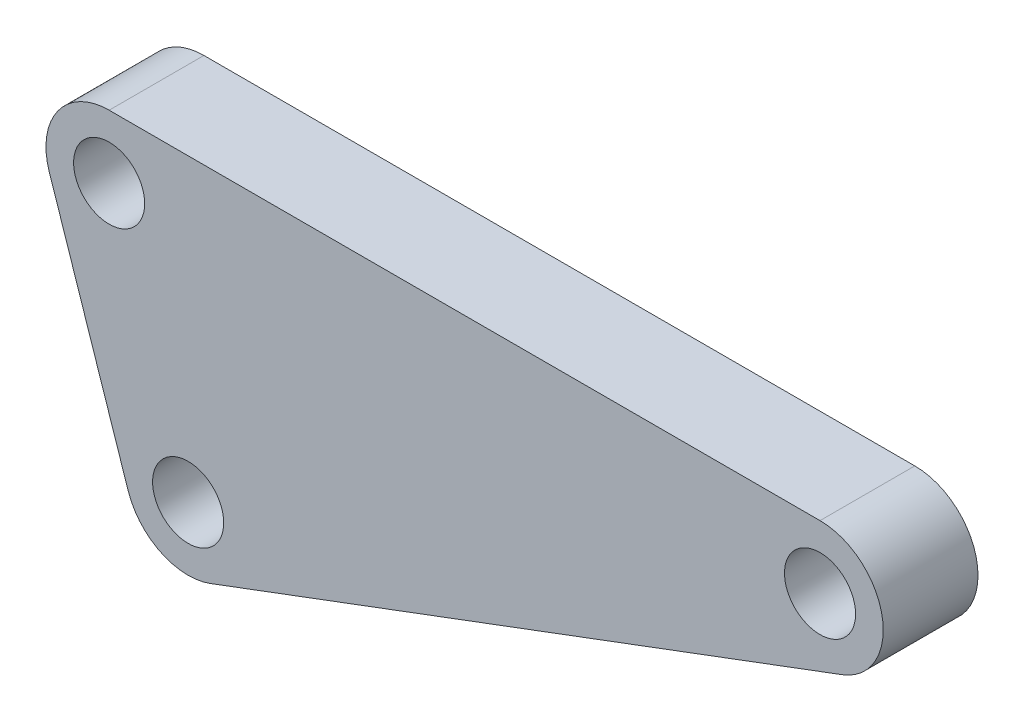
SolidWorks part; units mm, degrees
ref_plane "Front Plane" through (0, 0, 0) normal (0, 0, 1) x (1, 0, 0)
ref_plane "Top Plane" through (0, 0, 0) normal (0, 1, 0) x (1, 0, 0)
ref_plane "Right Plane" through (0, 0, 0) normal (1, 0, 0) x (0, 0, -1)
sketch "Sketch1" plane through (0, 0, 0) normal (0, 0, 1) x (1, 0, 0)
  line L0 (0, 0) -> (0, 6062.6861) construction
  line L1 (0, 0) -> (6062.6861, 0) construction
  line L2 (-5, 19) -> (40, 19)
  line L3 (-8.7947, 13.7351) -> (-3.7947, -1.2649)
  line L4 (1.4045, -3.7453) -> (41.4045, 11.2547)
  line L5 (-5, 15) -> (40, 15) construction
  circle A0 centre (0, 0) radius 2.25
  circle A1 centre (-5, 15) radius 2.25
  circle A2 centre (40, 15) radius 2.25
  arc A3 (-5, 19) -> (-8.7947, 13.7351) centre (-5, 15) ccw
  arc A4 (41.4045, 11.2547) -> (40, 19) centre (40, 15) ccw
  arc A5 (-3.7947, -1.2649) -> (1.4045, -3.7453) centre (0, 0) ccw
  dimension "D1" = 4.5
  dimension "D6" = 8
  dimension "D2" = 15
  dimension "D4" = 40
  dimension "D5" = 5
extrude "Boss-Extrude1" add sketch "Sketch1" along normal blind 6
